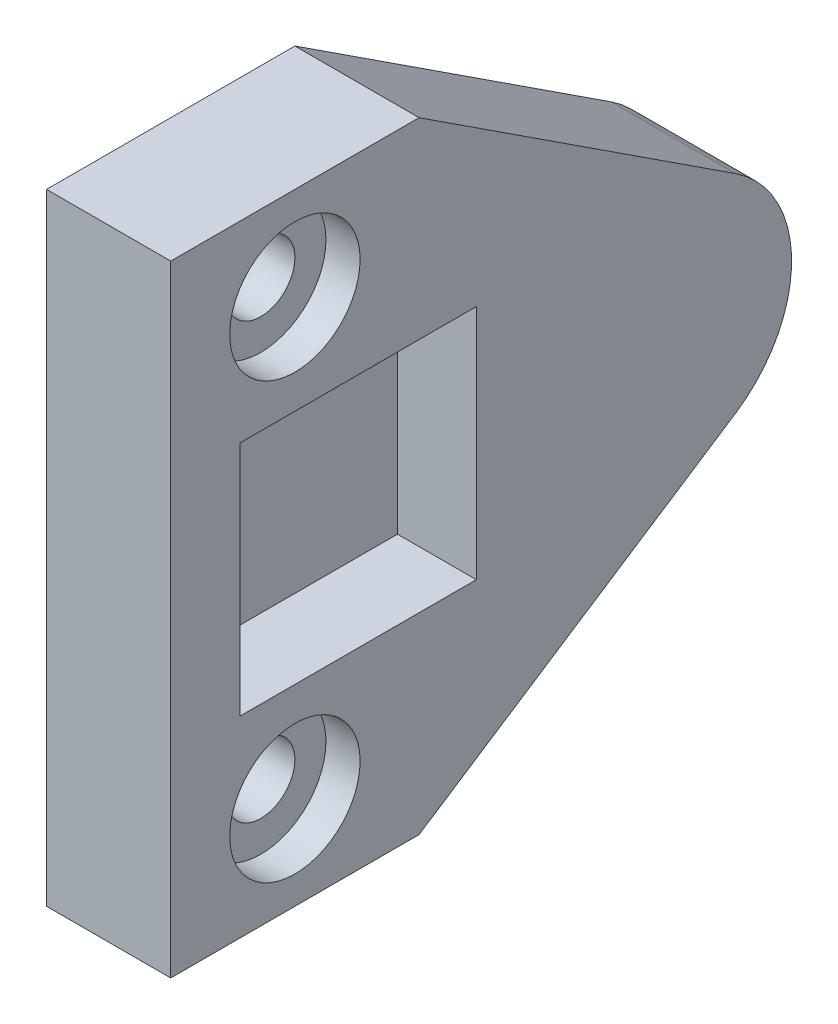
SolidWorks part; units mm, degrees
ref_plane "Front Plane" through (0, 0, 0) normal (0, 0, 1) x (1, 0, 0)
ref_plane "Top Plane" through (0, 0, 0) normal (0, 1, 0) x (1, 0, 0)
ref_plane "Right Plane" through (0, 0, 0) normal (1, 0, 0) x (0, 0, -1)
sketch "Sketch1" plane through (0, 0, 0) normal (1, 0, 0) x (0, 0, -1)
  line L0 (0, 25) -> (25.4668, 8.3734)
  line L1 (-20, -25) -> (0, -25)
  line L2 (-20, -25) -> (-20, 25)
  line L3 (-20, 25) -> (0, 25)
  line L4 (0, -25) -> (0, 25)
  line L5 (-10, 25) -> (-10, -25) construction
  line L6 (-20, 0) -> (0, 0) construction
  line L7 (25.4668, -8.3734) -> (0, -25)
  arc A0 (25.4668, 8.3734) -> (25.4668, -8.3734) centre (20, 0) cw
  point P0 (-10, 0)
  point P7 (0, 0)
  point P8 (0, 0)
  point P9 (0, 0)
  point P10 (10.6553, 0)
  dimension "D3" = 10
  dimension "D4" = 50
  dimension "D1" = 50
  dimension "D2" = 20
extrude "Boss-Extrude1" add sketch "Sketch1" along normal blind 10 contours L1 L4 L3 L2 | A0 L0 L4 L7
hole_wizard "CBORE for M5 SBHCS1" positions "Sketch3" profile "Sketch4" counterbore size "M5" standard "ANSI Metric" end condition through all
sketch "Sketch3" plane through (10, 0, 0) normal (1, 0, 0) x (0, 0, -1)
  line L0 (-10, 17.5) -> (-10, -17.5) construction
  line L3 (-10, 0) -> (0, 0) construction
  line L6 (-10, 25) -> (-10, 17.5) construction
  line L7 (-20, 25) -> (0, 25) construction
  point P0 (-10, 17.5)
  point P2 (-10, -17.5)
  dimension "D1" = 35
sketch "Sketch4" plane through (10, 17.5, 10) normal (0, 1, 0) x (0, 0, -1)
  line L0 (0, 0) -> (0, 10)
  line L1 (0, 10) -> (2.75, 10)
  line L3 (2.75, 10) -> (2.75, 2.75)
  line L4 (2.75, 2.75) -> (5.25, 2.75)
  line L5 (5.25, 2.75) -> (5.25, 0)
  line L7 (5.25, 0) -> (0, 0)
  line L11 (0, -6.35) -> (0, 107.95) construction
  dimension "Thru Hole Dia." = 5.5
  dimension "Thru Hole Depth" = 10
  dimension "C'Bore Dia." = 10.5
  dimension "C'Bore Depth" = 2.75
sketch "Sketch5" plane through (10, 0, 0) normal (1, 0, 0) x (0, 0, -1)
  line L1 (-14.4406, 9.525) -> (4.6094, 9.525)
  line L2 (-14.4406, 9.525) -> (-14.4406, -9.525)
  line L3 (-14.4406, -9.525) -> (4.6094, -9.525)
  line L4 (4.6094, 9.525) -> (4.6094, -9.525)
  line L5 (-4.9156, -9.525) -> (-4.9156, 9.525) construction
  line L6 (-14.4406, 0) -> (4.6094, 0) construction
  point P4 (-4.9156, 0)
  point P168 (-4.9156, 0)
  dimension "D1" = 19.05
extrude "Cut-Extrude1" cut sketch "Sketch5" against normal blind 6.35
